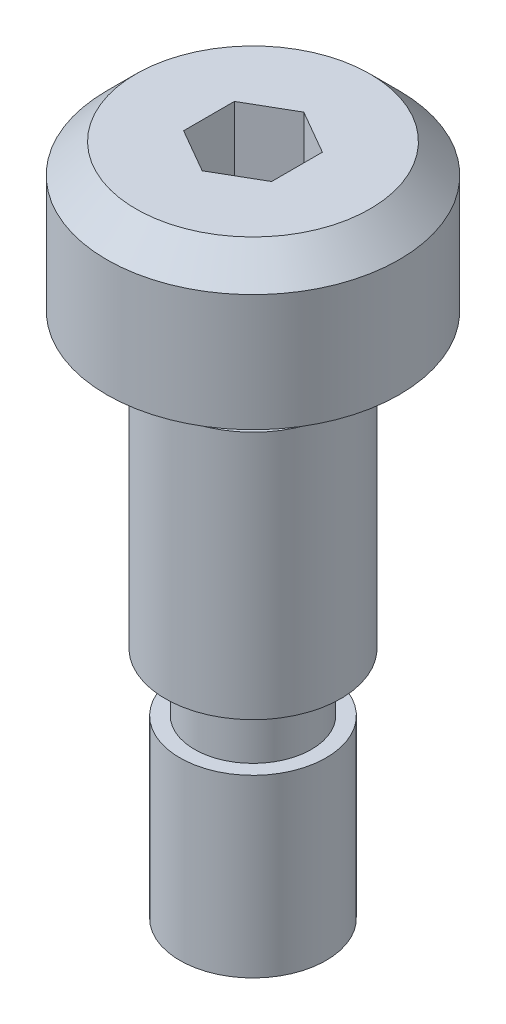
SolidWorks part; units mm, degrees
ref_plane "Plane1" through (0, 0, 0) normal (0, 0, 1) x (1, 0, 0)
ref_plane "Plane2" through (0, 0, 0) normal (0, 1, 0) x (1, 0, 0)
ref_plane "Plane3" through (0, 0, 0) normal (1, 0, 0) x (0, 0, -1)
other "Configuration Table"
sketch "Sketch2" plane through (0, 0, 0) normal (0, 0, 1) x (1, 0, 0)
  line L0 (0, 0) -> (7.9375, 0)
  line L1 (7.9375, 0) -> (7.9375, 6.35)
  line L2 (7.9375, 6.35) -> (6.35, 7.9375)
  line L3 (6.35, 7.9375) -> (0, 7.9375)
  line L4 (0, 7.9375) -> (0, 0)
  line L5 (0, 0) -> (0, 103.0583) construction
  dimension "D1" = 6.35
  dimension "D2" = 6.35
  dimension "D3" = 7.9375
  dimension "D4" = 135
revolve "Base-Revolve" add sketch "Sketch2" angle 360 about L5
sketch "Sketch3" plane through (0, 0, 0) normal (0, 0, 1) x (1, 0, 0)
  line L0 (0, 0) -> (0, 100) construction
  line L1 (0, -28.575) -> (3.9688, -28.575)
  line L2 (3.9688, -28.575) -> (3.9688, -19.05)
  line L3 (3.9688, -19.05) -> (3.175, -19.05)
  line L4 (3.175, -19.05) -> (3.175, -15.875)
  line L5 (3.175, -15.875) -> (4.7625, -15.875)
  line L6 (4.7625, -15.875) -> (4.7625, -2.3622)
  line L7 (4.7625, -2.3622) -> (4.445, -2.3622)
  line L8 (4.445, -2.3622) -> (4.445, 0)
  line L9 (4.445, 0) -> (0, 0)
  line L10 (0, 0) -> (0, -28.575)
  dimension "D1" = 15.875
  dimension "D2" = 12.7
  dimension "D3" = 7.9375
  dimension "D4" = 6.35
  dimension "D5" = 9.525
  dimension "D6" = 8.89
  dimension "D7" = 3.175
revolve "Boss-Revolve1" add sketch "Sketch3" angle 360 about L0
ref_plane "Plane4" through (0, 6.35, 0) normal (0, 1, 0) x (-1, 0, 0)
sketch "Sketch4" plane through (0, 7.9375, 0) normal (0, 1, 0) x (-1, 0, 0)
  line L0 (2.3876, 1.3785) -> (0, 2.757)
  line L1 (0, 2.757) -> (-2.3876, 1.3785)
  line L2 (-2.3876, 1.3785) -> (-2.3876, -1.3785)
  line L3 (-2.3876, -1.3785) -> (0, -2.757)
  line L4 (0, -2.757) -> (2.3876, -1.3785)
  line L5 (2.3876, -1.3785) -> (2.3876, 1.3785)
extrude "Cut-Extrude1" cut sketch "Sketch4" against normal blind 3.5814
